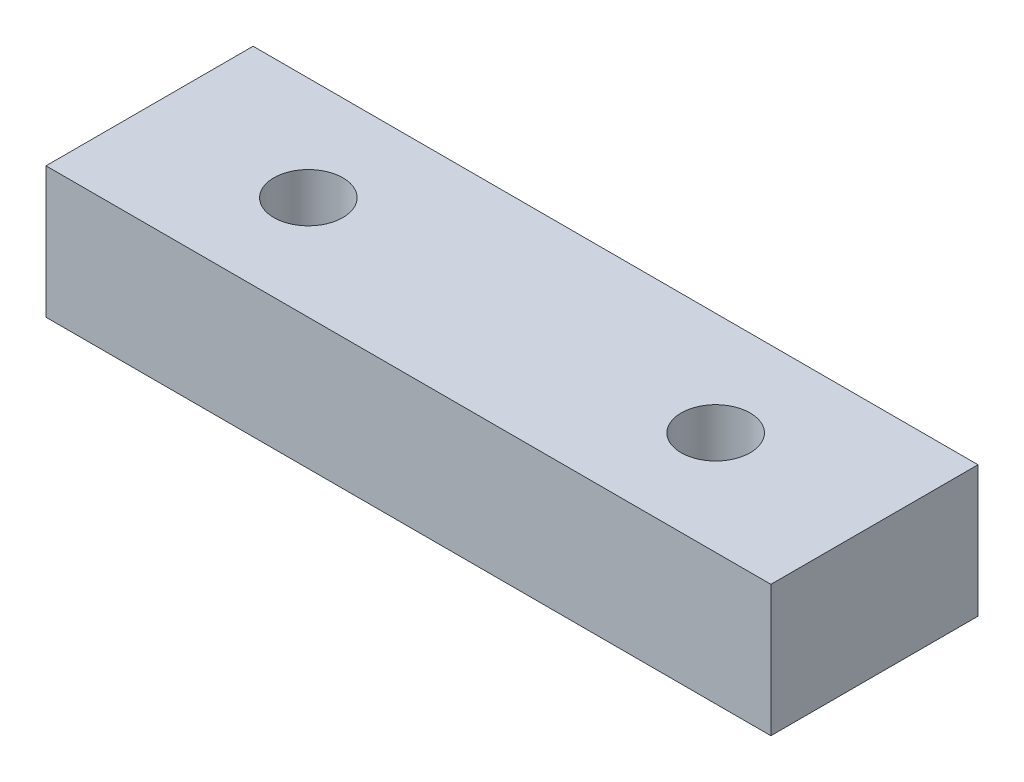
SolidWorks part; units mm, degrees
ref_plane "Front Plane" through (0, 0, 0) normal (0, 0, 1) x (1, 0, 0)
ref_plane "Top Plane" through (0, 0, 0) normal (0, 1, 0) x (1, 0, 0)
ref_plane "Right Plane" through (0, 0, 0) normal (1, 0, 0) x (0, 0, -1)
sketch "Sketch1" plane through (0, 0, 0) normal (0, 1, 0) x (1, 0, 0)
  line L0 (-56.6102, 9.6) -> (-56.6102, 3.6) construction
  line L1 (-73.0102, 3.6) -> (-52.0102, 3.6)
  line L2 (-73.0102, 3.6) -> (-73.0102, 9.6)
  line L3 (-73.0102, 9.6) -> (-52.0102, 9.6)
  line L4 (-52.0102, 3.6) -> (-52.0102, 9.6)
  line L5 (-73.0102, 6.6) -> (-52.0102, 6.6) construction
  line L6 (-68.4102, 9.6) -> (-68.4102, 3.6) construction
  circle A0 centre (-56.6102, 6.6) radius 1
  circle A1 centre (-68.4102, 6.6) radius 1
  dimension "D1" = 21
  dimension "D2" = 4.6
  dimension "D3" = 4.6
extrude "Boss-Extrude1" add sketch "Sketch1" along normal blind 3.8
